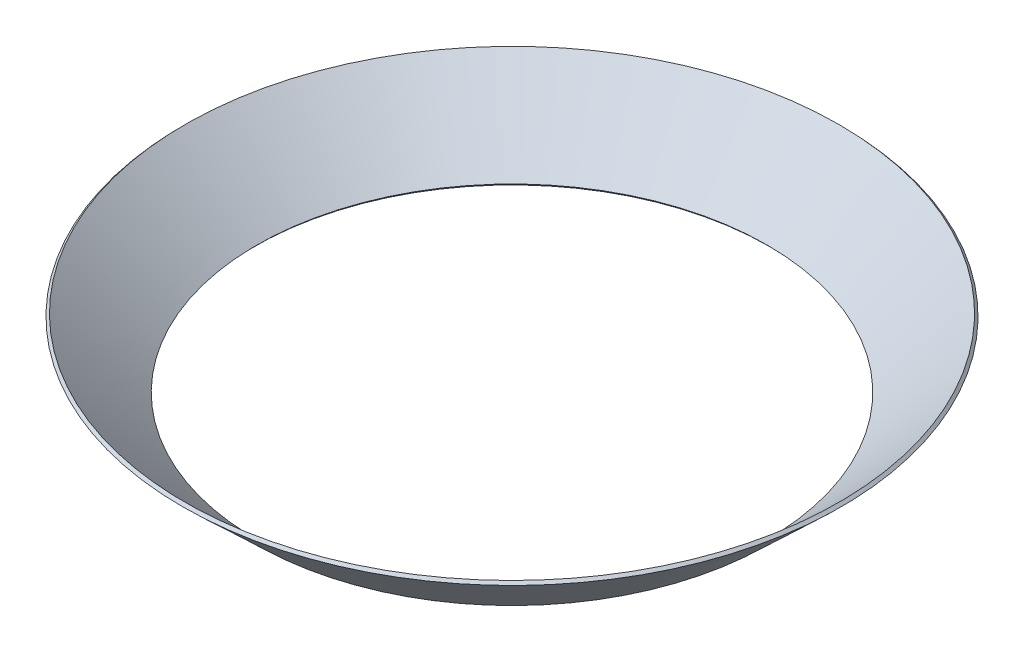
SolidWorks part; units mm, degrees
ref_plane "Front Plane" through (0, 0, 0) normal (0, 0, 1) x (1, 0, 0)
ref_plane "Top Plane" through (0, 0, 0) normal (0, 1, 0) x (1, 0, 0)
ref_plane "Right Plane" through (0, 0, 0) normal (1, 0, 0) x (0, 0, -1)
sketch "Sketch1" plane through (0, 0, 0) normal (1, 0, 0) x (0, 0, -1)
  line L0 (26.0878, 274.978) -> (26.0878, 232.1195) construction
  line L2 (40.135, 302.9291) -> (40.135, 295.6281) construction
  line L5 (0, 324) -> (3.2968, 324) construction
  line L7 (21.6442, 186.0993) -> (0, 186.0993) construction
  line L9 (26.0878, 262.3641) -> (26.0878, 259.4973) construction
  line L16 (0, 0) -> (51.9362, 327.9125) construction
  line L17 (0, 324) -> (0, 332) construction
  line L18 (26.0878, 274.978) -> (26.0878, 268.978) construction
  line L19 (26.0878, 268.978) -> (26.0878, 248.978) construction
  line L20 (26.0878, 268.978) -> (42.6019, 268.978) construction
  line L21 (26.0878, 274.978) -> (43.5522, 274.978) construction
  line L22 (26.0878, 248.978) -> (39.4342, 248.978) construction
  line L23 (0, 0) -> (-51.9362, 327.9125) construction
  line L24 (-47.4003, 299.274) -> (-47.4003, 268.978) construction
  line L25 (-47.4003, 268.978) -> (-42.6019, 268.978) construction
  line L26 (40.135, 295.6281) -> (40.435, 295.6281) construction
  line L27 (0, 76.96) -> (400, 76.96) construction
  line L28 (0, 76.96) -> (-400, 76.96) construction
  line L29 (-200, 76.96) -> (-200, 183.96) construction
  line L30 (200, 76.96) -> (200, 183.96) construction
  line L31 (-200, 183.96) -> (-200, 182.57) construction
  line L32 (-200, 182.57) -> (400, 182.57) construction
  line L33 (-200, 182.57) -> (-400, 182.57) construction
  line L36 (21.6442, 186.0993) -> (21.6442, 226.0993) construction
  line L37 (0, 324) -> (0, 186.1152) construction
  line L38 (0, 186.1152) -> (0, 186.0993)
  line L39 (0, 0) -> (-2, 0) construction
  line L40 (-2, 0) -> (49.9843, 328.2157) construction
  line L41 (51.9362, 327.9125) -> (49.9362, 327.9125) construction
  line L42 (26.0878, 274.978) -> (26.3878, 274.978) construction
  line L43 (26.0878, 274.978) -> (26.0878, 273.978) construction
  line L44 (26.2311, 276.2681) -> (26.5311, 276.2681) construction
  line L45 (26.6611, 277.4147) -> (26.9611, 277.4147) construction
  line L46 (27.2344, 278.5614) -> (27.5344, 278.5614) construction
  line L47 (27.9512, 279.4215) -> (28.2512, 279.4215) construction
  line L48 (28.9545, 280.5682) -> (29.2545, 280.5682) construction
  line L49 (29.8146, 281.4282) -> (30.1146, 281.4282) construction
  line L50 (30.8179, 282.4316) -> (31.1179, 282.4316) construction
  line L51 (31.8213, 283.2917) -> (32.1213, 283.2917) construction
  line L52 (32.8246, 284.2951) -> (33.1246, 284.2951) construction
  line L53 (33.8281, 285.2984) -> (34.1281, 285.2984) construction
  line L54 (34.9748, 286.3018) -> (35.2748, 286.3018) construction
  line L55 (35.9781, 287.3051) -> (36.2781, 287.3051) construction
  line L56 (36.8382, 288.1652) -> (37.1382, 288.1652) construction
  line L57 (37.8416, 289.3119) -> (38.1416, 289.3119) construction
  line L58 (38.5582, 290.4586) -> (38.8582, 290.4586) construction
  line L59 (39.1315, 291.7487) -> (39.4315, 291.7487) construction
  line L60 (39.5617, 292.8954) -> (39.8617, 292.8954) construction
  line L61 (39.8483, 294.0421) -> (40.1483, 294.0421) construction
  line L63 (40.135, 302.9291) -> (40.435, 302.9291) construction
  line L64 (26.0878, 273.978) -> (26.3878, 273.978) construction
  line L68 (0, 332) -> (36.0261, 332) construction
  line L69 (36.0261, 332) -> (36.0261, 309.4264) construction
  line L70 (36.0261, 309.4264) -> (48.951, 321.6917) construction
  line L71 (36.0261, 309.4264) -> (49.0083, 309.4264) construction
  line L73 (36.0261, 309.4264) -> (46.0928, 318.9794) construction
  line L74 (46.0928, 318.9794) -> (46.0928, 386.8005) construction
  line L75 (46.0928, 318.9794) -> (19.4833, 320.3739) construction
  line L76 (19.4833, 320.3739) -> (20.8454, 323.7133) construction
  line L77 (19.4833, 320.3739) -> (28.7426, 316.597) construction
  line L78 (19.4833, 320.3739) -> (10.2239, 324.1508) construction
  line L79 (10.2239, 324.1508) -> (9.7753, 323.0511) construction
  line L80 (28.7426, 316.597) -> (28.4187, 315.803) construction
  arc A0 (-298.7691, 144.7791) -> (305.6579, 129.6043) centre (0, 0) cw construction
  spline S0 degree 3 poles (21.6442, 226.0993) (22.3362, 225.9573) (23.1249, 226.5484) (24.2443, 227.206) (25.0066, 227.971) (25.5796, 228.9526) (25.8622, 230.3928) (26.0228, 231.4438) (26.0878, 232.1195) knots 0 0 0 0 0.223849 0.348959 0.47164 0.61152 0.754586 1 1 1 1 construction
  spline S1 degree 3 poles (3.2968, 324) (4.1972, 323.8396) (5.699, 323.816) (7.6935, 323.4297) (9.2722, 323.1563) (10.7507, 322.8538) (12.1816, 322.5577) (13.6372, 322.313) (14.8643, 321.9117) (15.9115, 321.5662) (16.81, 321.2491) (17.7339, 321.0149) (18.8379, 320.6416) (19.931, 320.1935) (21.0686, 319.6948) (22.141, 319.2627) (23.2156, 318.6856) (24.4371, 318.1163) (25.6762, 317.3518) (27.1066, 316.7518) (28.4318, 315.7832) (29.7322, 314.8939) (31.058, 313.93) (32.1959, 312.8581) (33.3378, 311.8503) (34.4539, 310.9646) (35.3895, 309.8867) (36.5078, 309.0949) (37.2942, 308.0208) (38.1233, 307.1238) (38.9048, 306.0961) (39.4724, 304.6349) (40.2774, 303.734) (40.135, 302.9291) knots 0 0 0 0 0.061585 0.100795 0.136831 0.1697 0.202569 0.235438 0.269088 0.289473 0.309858 0.333319 0.353706 0.388423 0.412965 0.437514 0.46634 0.495168 0.528354 0.564387 0.59925 0.638593 0.670824 0.709635 0.743897 0.773612 0.805519 0.839783 0.864953 0.89467 0.922395 0.951224 1 1 1 1 construction
  spline S2 degree 3 poles (40.135, 295.6188) (39.9636, 294.7131) (39.7869, 293.3689) (39.1095, 291.6901) (38.6019, 290.4599) (37.8418, 289.2392) (36.9195, 288.2279) (35.9232, 287.2651) (34.974, 286.2515) (33.8311, 285.3463) (32.8233, 284.2966) (31.8701, 283.2868) (30.7668, 282.4387) (29.8742, 281.4644) (28.8604, 280.5152) (28.0567, 279.5119) (27.1438, 278.5569) (26.4968, 277.0287) (26.0081, 275.8567) (26.0878, 274.978) knots 0 0 0 0 0.108356 0.15601 0.210945 0.263562 0.322855 0.370186 0.425399 0.484692 0.539909 0.595126 0.646549 0.701764 0.749093 0.808384 0.85195 0.901837 1 1 1 1 construction
  dimension "D2" = 2
  dimension "D4" = 8
  dimension "D5" = 2
  dimension "D6" = 36.0261
  dimension "D8" = 70.809
  dimension "D9" = 6
  dimension "D10" = 20
  dimension "D11" = 1.1877
  dimension "D12" = 0.8575
  dimension "D13" = 255.04
  dimension "D14" = 107
  dimension "D15" = 107
  dimension "D16" = 332
  dimension "D17" = 105.61
  dimension "D18" = 105.61
  dimension "D19" = 40
  dimension "D20" = 90
  dimension "D21" = 46.5
sketch "reflector" plane through (0, 0, 0) normal (1, 0, 0) x (0, 0, -1)
  line L0 (0, 0) -> (0, 354.6797) construction
  line L13 (36.0261, 309.4264) -> (35.6819, 309.7891)
  line L14 (46.0928, 318.9794) -> (45.7486, 319.3421)
  line L15 (36.0261, 309.4264) -> (46.0928, 318.9794)
  line L16 (35.6819, 309.7891) -> (45.7486, 319.3421)
revolve "Revolve10" add sketch "reflector" angle 360 about L0
